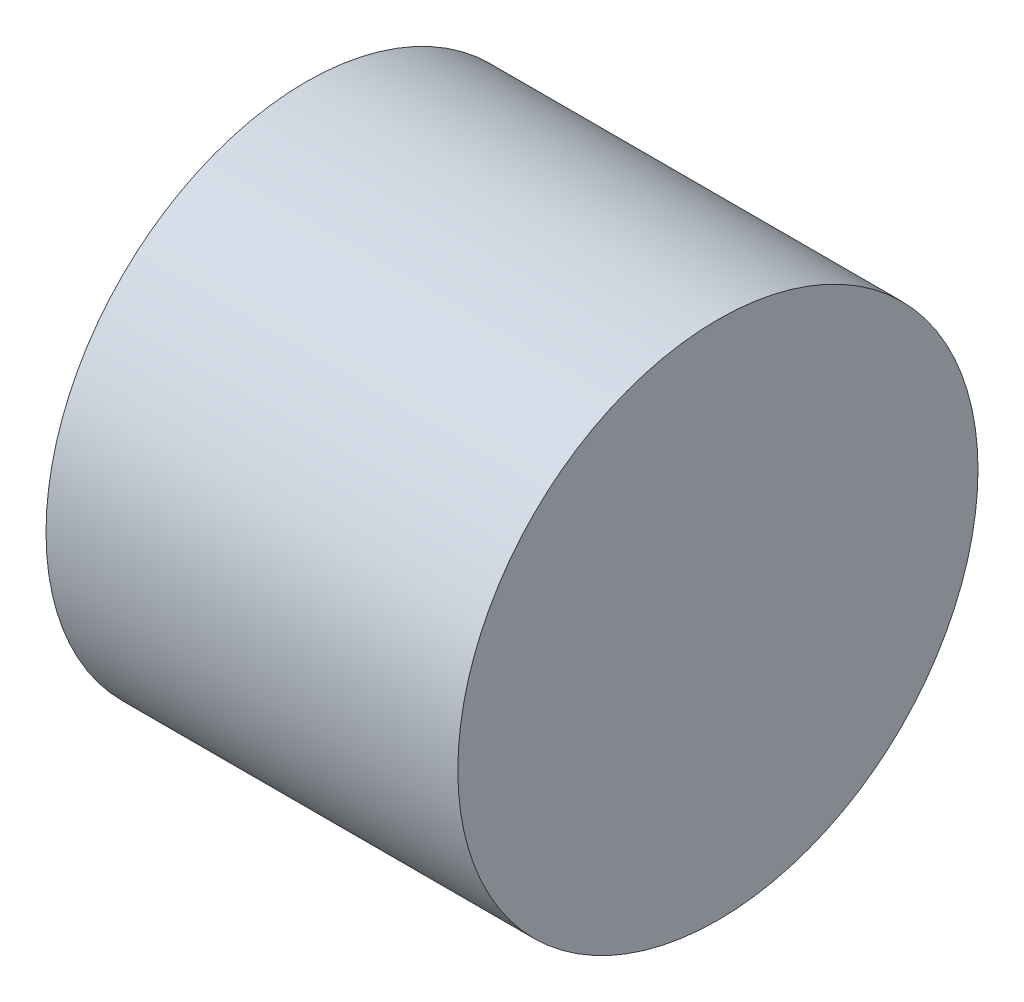
SolidWorks part; units mm, degrees
ref_plane "Front Plane" through (0, 0, 0) normal (0, 0, 1) x (1, 0, 0)
ref_plane "Top Plane" through (0, 0, 0) normal (0, 1, 0) x (1, 0, 0)
ref_plane "Right Plane" through (0, 0, 0) normal (1, 0, 0) x (0, 0, -1)
ref_plane "PX_p47_40" through (47.4, 0, 0) normal (1, 0, 0) x (0, 0, -1)
sketch "Body_Sk1" plane through (47.4, 0, 0) normal (1, 0, 0) x (0, 0, -1)
  circle A0 centre (22.5, -18) radius 6
extrude "Body" add sketch "Body_Sk1" against normal blind 9.5
